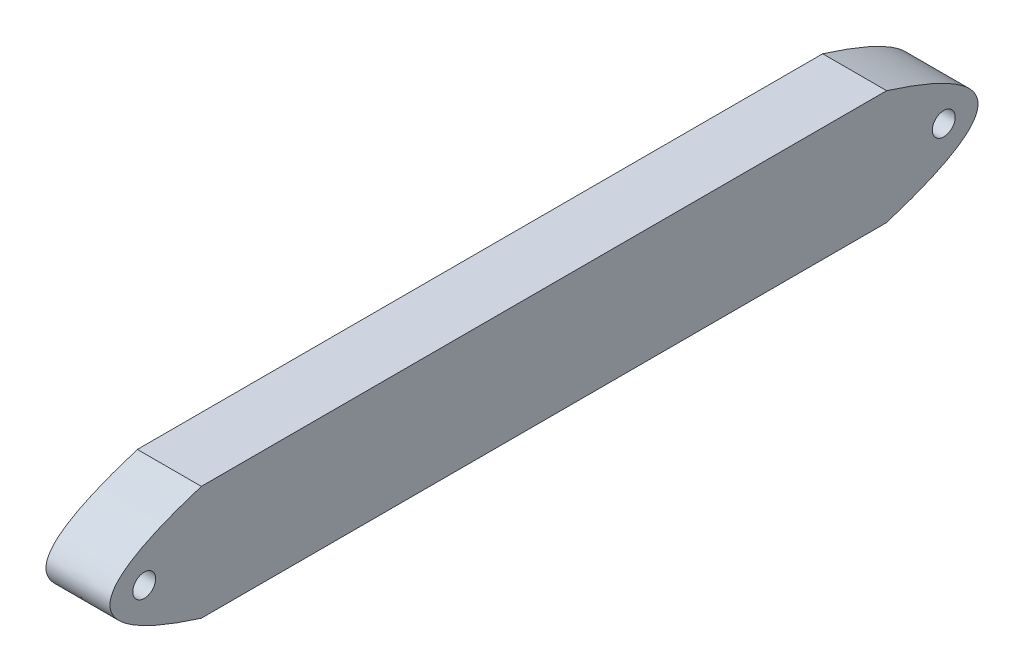
SolidWorks part; units mm, degrees
ref_plane "Front Plane" through (0, 0, 0) normal (0, 0, 1) x (1, 0, 0)
ref_plane "Top Plane" through (0, 0, 0) normal (0, 1, 0) x (1, 0, 0)
ref_plane "Right Plane" through (0, 0, 0) normal (1, 0, 0) x (0, 0, -1)
sketch "Sketch1" plane through (0, 0, 0) normal (1, 0, 0) x (0, 0, -1)
  line L0 (-150, 25) -> (150, 25)
  line L1 (-150, -25) -> (150, -25)
  circle A0 centre (-175, 0) radius 5
  circle A1 centre (175, 0) radius 5
  spline S0 degree 2 poles (150, 25) (230, 0) (150, -25) knots 0 0 0 1 1 1
  spline S1 degree 2 poles (-150, 25) (-230, 0) (-150, -25) knots 0 0 0 1 1 1
  dimension "D8" = 10
  dimension "D1" = 300
  dimension "D2" = 50
  dimension "D3" = 25
  dimension "D4" = 40
  dimension "D5" = 40
  dimension "D6" = 15
  dimension "D7" = 0
  dimension "D9" = 15
extrude "Boss-Extrude1" add sketch "Sketch1" along normal blind 28
